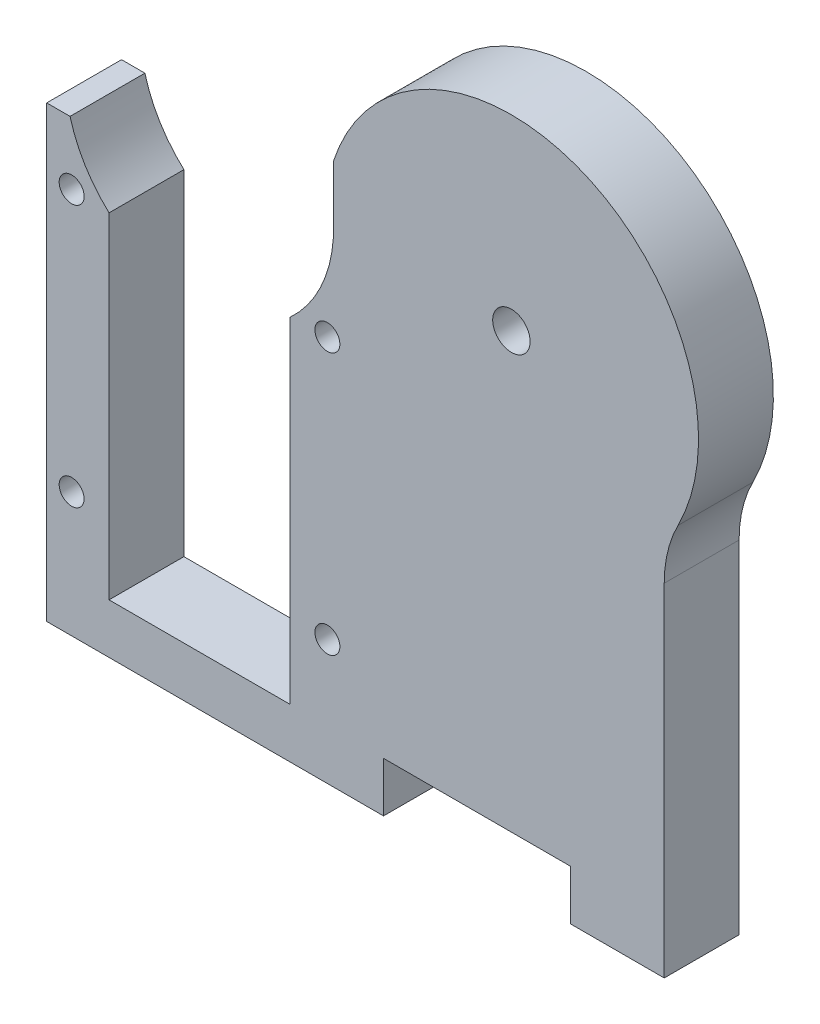
SolidWorks part; units mm, degrees
ref_plane "Спереди" through (0, 0, 0) normal (0, 0, 1) x (1, 0, 0)
ref_plane "Сверху" through (0, 0, 0) normal (0, 1, 0) x (1, 0, 0)
ref_plane "Справа" through (0, 0, 0) normal (1, 0, 0) x (0, 0, -1)
other "Configuration Table"
sketch "Эскиз1" plane through (0, 0, 0) normal (0, 0, 1) x (1, 0, 0)
  line L0 (12.25, 0) -> (12.25, 21.8319) construction
  line L2 (0, 0) -> (0, 32)
  line L5 (0, 16.5) -> (16.6505, 16.5) construction
  line L6 (5, 0) -> (5, 26.8668)
  line L7 (19.5, 0) -> (19.5, 26.8668)
  line L10 (0, 0) -> (0, -4)
  line L11 (0, -4) -> (49.5, -4)
  line L12 (49.5, -4) -> (49.5, 23.405)
  line L14 (5, 0) -> (19.5, 0)
  line L15 (1.8721, 32) -> (0, 32)
  line L16 (22.9955, 35.1157) -> (22.9955, 39.474)
  line L17 (37.25, 34.804) -> (12.25, 34.804) construction
  line L18 (24.75, 34.804) -> (24.75, -4) construction
  circle A0 centre (2, 27) radius 1
  circle A1 centre (22.5, 27) radius 1
  circle A2 centre (22.5, 6) radius 1
  circle A3 centre (2, 6) radius 1
  arc A4 (1.8721, 32) -> (5, 26.8668) centre (12.25, 34.804) ccw
  arc A5 (19.5, 26.8668) -> (22.9955, 35.1157) centre (12.25, 34.804) ccw
  circle A6 centre (37.25, 34.804) radius 1.5
  arc A7 (50.6, 27.9646) -> (22.9955, 39.474) centre (37.25, 34.804) ccw
  arc A8 (49.5, 23.405) -> (50.6, 27.9646) centre (59.5, 23.405) cw
  point P32 (0, 0)
  dimension "D3" = 2
  dimension "D9" = 21.5
  dimension "D6" = 3
  dimension "D13" = 30
  dimension "D14" = 10
  dimension "D2" = 25
  dimension "D4" = 21
  dimension "D5" = 20.5
  dimension "D7" = 2
  dimension "D8" = 4
  dimension "D10" = 14.5
  dimension "D11" = 36
  dimension "D12" = 6
extrude "Бобышка-Вытянуть1" add sketch "Эскиз1" along normal blind 6
sketch "Эскиз3" plane through (0, 0, 6) normal (0, 0, 1) x (1, 0, 0)
  line L0 (0, -4) -> (49.5, -4) construction
  line L1 (27, -4) -> (42, -4)
  line L2 (27, -4) -> (27, 0)
  line L3 (27, 0) -> (42, 0)
  line L4 (42, -4) -> (42, 0)
  line L6 (0, 32) -> (0, -4) construction
  dimension "D1" = 4
  dimension "D2" = 15
  dimension "D3" = 27
extrude "Вырез-Вытянуть1" cut sketch "Эскиз3" against normal blind 10
